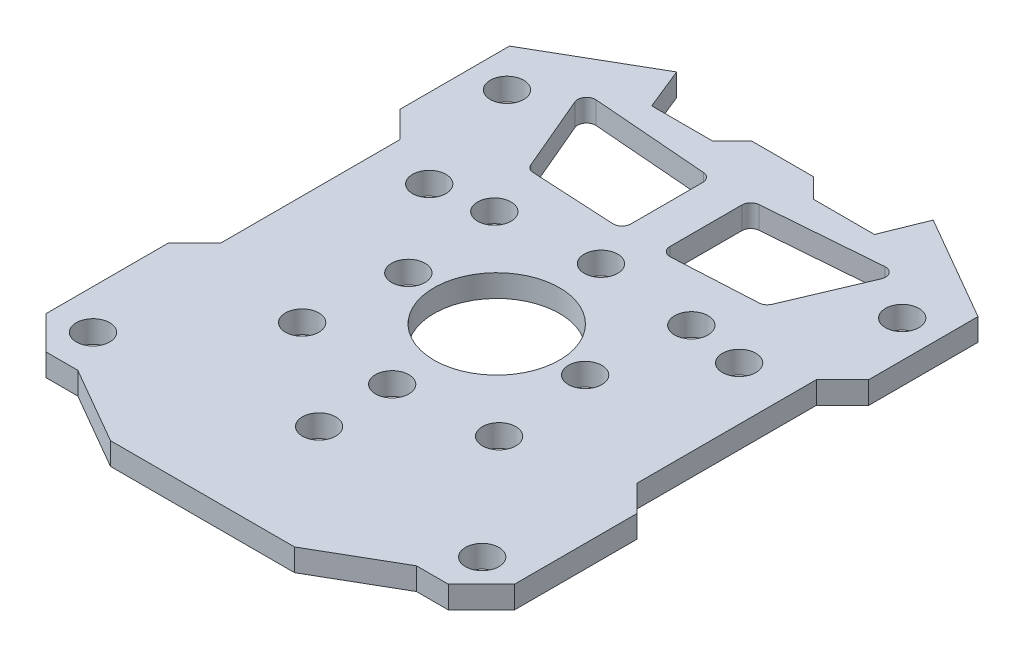
SolidWorks part; units mm, degrees
ref_plane "Front Plane" through (0, 0, 0) normal (0, 0, 1) x (1, 0, 0)
ref_plane "Top Plane" through (0, 0, 0) normal (0, 1, 0) x (1, 0, 0)
ref_plane "Right Plane" through (0, 0, 0) normal (1, 0, 0) x (0, 0, -1)
sketch "Sketch1" plane through (0, 0, 0) normal (0, 1, 0) x (1, 0, 0)
  line L0 (0, 0) -> (0, 52) construction
  line L1 (2.75, 52) -> (-2.75, 52)
  line L2 (-2.75, 52) -> (-4.5, 50.25)
  line L3 (-4.5, 50.25) -> (-9.9849, 50.25)
  line L4 (-9.9849, 50.25) -> (-11.5, 54)
  line L5 (-11.5, 54) -> (-21, 48.5152)
  line L6 (-21, 48.5152) -> (-21, 38.7198)
  line L7 (-21, 38.7198) -> (-18.65, 36.3698)
  line L8 (-18.65, 36.3698) -> (-18.65, 20.3198)
  line L9 (-18.65, 20.3198) -> (-21, 17.9698)
  line L10 (-21, 17.9698) -> (-21, 6.9698)
  line L11 (-21, 6.9698) -> (-18.0302, 4)
  line L12 (-18.0302, 4) -> (-15.1782, 4)
  line L13 (-15.1782, 4) -> (-8.25, 0)
  line L14 (-8.25, 0) -> (8.25, 0)
  line L15 (15.1782, 4) -> (8.25, 0)
  line L16 (18.0302, 4) -> (15.1782, 4)
  line L17 (21, 6.9698) -> (18.0302, 4)
  line L18 (21, 17.9698) -> (21, 6.9698)
  line L19 (18.65, 20.3198) -> (21, 17.9698)
  line L20 (18.65, 36.3698) -> (18.65, 20.3198)
  line L21 (21, 38.7198) -> (18.65, 36.3698)
  line L22 (21, 48.5152) -> (21, 38.7198)
  line L23 (11.5, 54) -> (21, 48.5152)
  line L24 (9.9849, 50.25) -> (11.5, 54)
  line L25 (4.5, 50.25) -> (9.9849, 50.25)
  line L26 (2.75, 52) -> (4.5, 50.25)
  line L27 (-18.0302, 4) -> (-25.0644, 4) construction
  line L28 (-18.65, 20.3198) -> (-34.6393, 20.3198) construction
  line L29 (-2.75, 52) -> (-4.9751, 52) construction
  line L30 (-11.5, 54) -> (-20.2691, 54) construction
  line L31 (-8.25, 0) -> (-15.4287, 0) construction
  dimension "D4" = 5.5
  dimension "D1" = 45
  dimension "D2" = 45
  dimension "D3" = 42
  dimension "D5" = 16.5
  dimension "D6" = 4.2
  dimension "D7" = 54
  dimension "D8" = 45
  dimension "D9" = 23
  dimension "D10" = 1.75
  dimension "D11" = 52
  dimension "D12" = 30
  dimension "D13" = 20.75
  dimension "D14" = 11
  dimension "D15" = 4
  dimension "D16" = 37.3
  dimension "D17" = 82
  dimension "D18" = 30
extrude "Boss-Extrude1" add sketch "Sketch1" along normal blind 2
sketch "Sketch2" plane through (0, 2, 0) normal (0, 1, 0) x (1, 0, 0)
  line L0 (0, 0) -> (0, 52) construction
  line L1 (2.75, 52) -> (-2.75, 52) construction
  line L2 (0, 26.375) -> (-7.925, 26.375) construction
  line L3 (0, 17) -> (-8.8274, 17.7594) construction
  line L4 (-8.8274, 17.7594) -> (0, 26.375) construction
  line L5 (-8.8274, 17.7594) -> (-17.4431, 7.6272) construction
  line L6 (-17.4431, 7.6272) -> (0, 10.45) construction
  line L7 (0, 35.72) -> (-8.8297, 34.9883) construction
  line L8 (-8.8297, 34.9883) -> (0, 26.375) construction
  line L9 (-8.8297, 34.9883) -> (-13.8907, 34.2129) construction
  line L10 (-7.925, 26.375) -> (-13.8907, 34.2129) construction
  line L11 (-17.7136, 45.0059) -> (-13.8907, 34.2129) construction
  line L12 (-17.7136, 45.0059) -> (0, 35.72) construction
  circle A0 centre (-17.7136, 45.0059) radius 1.5
  circle A1 centre (-17.4431, 7.6272) radius 1.5
  circle A2 centre (0, 10.45) radius 1.5
  circle A3 centre (0, 17) radius 1.5
  circle A4 centre (0, 26.375) radius 5.625
  circle A5 centre (-8.8274, 17.7594) radius 1.5
  circle A6 centre (-7.925, 26.375) radius 1.5
  circle A7 centre (-13.8907, 34.2129) radius 1.5
  circle A8 centre (-8.8297, 34.9883) radius 1.5
  circle A9 centre (0, 35.72) radius 1.5
  point P20 (-5.625, 26.375)
  point P26 (-6.425, 26.375)
  point P27 (0, 32)
  point P28 (0, 32)
  point P29 (0, 34.22)
  point P30 (0, 18.5)
  point P31 (0, 20.75)
  point P32 (-7.3329, 17.6308)
  point P33 (0, 11.95)
  point P34 (-1.4945, 17.1286)
  point P35 (-7.7539, 18.8071)
  point P36 (-4.0255, 22.4461)
  point P37 (-9.7991, 16.6166)
  point P38 (-16.4714, 8.7699)
  point P39 (-15.9623, 7.8669)
  point P40 (-1.4807, 10.2104)
  point P41 (-12.408, 34.4401)
  point P42 (-10.3124, 34.7611)
  point P43 (-12.9822, 33.0193)
  point P44 (-8.8335, 27.5686)
  point P45 (-17.2128, 43.5919)
  point P46 (-14.3915, 35.6268)
  point P47 (-16.3851, 44.3094)
  point P48 (-1.3285, 36.4164)
  point P50 (0, 0)
  dimension "D1" = 3
  dimension "D2" = 11.25
  dimension "D3" = 0.8
  dimension "D4" = 20
  dimension "D5" = 2.22
  dimension "D6" = 2.25
  dimension "D7" = 8.8
  dimension "D8" = 5.86
  dimension "D9" = 5.21
  dimension "D10" = 10.3
  dimension "D11" = 14.67
  dimension "D12" = 2.12
  dimension "D13" = 6.85
  dimension "D14" = 8.45
  dimension "D15" = 17
extrude "Cut-Extrude1" cut sketch "Sketch2" against normal up to surface (2 mm away) up to face at (0, 0, -29.4896)
mirror "Mirror1" about plane through (0, 0, 0) normal (1, 0, 0) of "Cut-Extrude1"
sketch "Sketch3" plane through (0, 2, 0) normal (0, 1, 0) x (1, 0, 0)
  line L0 (-2.4868, 47.397) -> (-12.935, 48.2248)
  line L1 (-13.7346, 47.1148) -> (-10.8201, 40.2479)
  line L2 (-10.1264, 39.7616) -> (-2.5927, 39.3587)
  line L3 (0, 39.22) -> (0, 47.2) construction
  line L4 (10.1264, 39.7616) -> (2.5927, 39.3587)
  line L5 (13.7346, 47.1148) -> (10.8201, 40.2479)
  line L6 (2.4868, 47.397) -> (12.935, 48.2248)
  line L7 (2.75, 52) -> (-2.75, 52) construction
  line L8 (-1.75, 46.5995) -> (-1.75, 40.1575)
  line L9 (1.75, 46.5995) -> (1.75, 40.1575)
  line L10 (-1.75, 39.3136) -> (0, 39.22) construction
  line L11 (0, 39.22) -> (1.75, 39.3136) construction
  line L12 (1.75, 47.3387) -> (0, 47.2) construction
  line L13 (0, 47.2) -> (-1.75, 47.3387) construction
  arc A0 (13.7346, 47.1148) -> (12.935, 48.2248) centre (12.9982, 47.4273) ccw
  arc A1 (10.1264, 39.7616) -> (10.8201, 40.2479) centre (10.0837, 40.5604) ccw
  arc A2 (-10.8201, 40.2479) -> (-10.1264, 39.7616) centre (-10.0837, 40.5604) ccw
  arc A3 (-12.935, 48.2248) -> (-13.7346, 47.1148) centre (-12.9982, 47.4273) ccw
  circle A4 centre (0, 35.72) radius 1.5 construction
  circle A5 centre (-8.8297, 34.9883) radius 1.5 construction
  circle A6 centre (-17.7136, 45.0059) radius 1.5 construction
  arc A7 (1.75, 40.1575) -> (2.5927, 39.3587) centre (2.55, 40.1575) ccw
  arc A8 (-1.75, 40.1575) -> (-2.5927, 39.3587) centre (-2.55, 40.1575) cw
  arc A9 (1.75, 46.5995) -> (2.4868, 47.397) centre (2.55, 46.5995) cw
  arc A10 (-1.75, 46.5995) -> (-2.4868, 47.397) centre (-2.55, 46.5995) ccw
  point P13 (14.25, 48.329)
  point P16 (10.625, 39.7883)
  point P19 (-10.625, 39.7883)
  point P22 (-14.25, 48.329)
  dimension "D1" = 0.8
  dimension "D9" = 0.8
  dimension "D2" = 3.5
  dimension "D3" = 4.8
  dimension "D4" = 28.5
  dimension "D5" = 21.25
  dimension "D6" = 4.8
  dimension "D7" = 4.8
  dimension "D8" = 3.5
extrude "Cut-Extrude2" cut sketch "Sketch3" against normal up to surface (2 mm away) up to face at (17.7136, 0, -43.5059)
